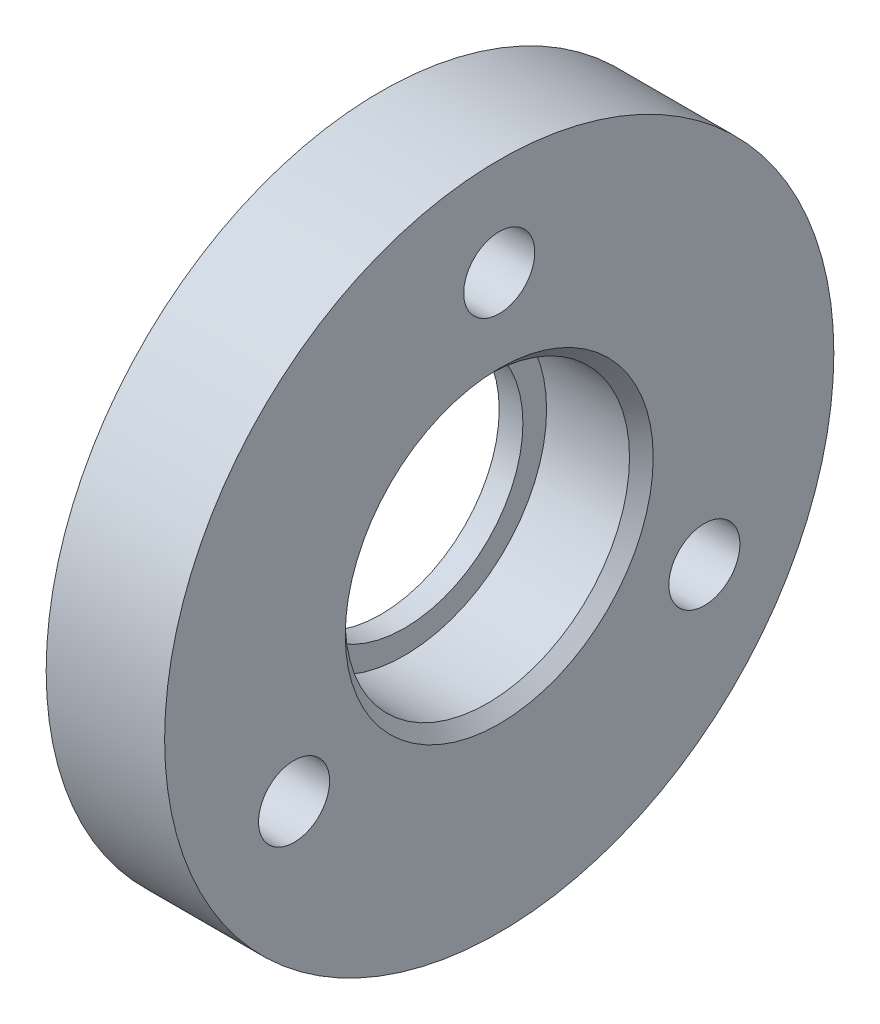
SolidWorks part; units mm, degrees
ref_plane "Front Plane" through (0, 0, 0) normal (1, 0, 0) x (0, 1, 0)
ref_plane "Top Plane" through (0, 0, 0) normal (0, 0, 1) x (0, 1, 0)
ref_plane "Right Plane" through (0, 0, 0) normal (0, 1, 0) x (-1, 0, 0)
sketch "Sketch3" plane through (0, 0, 0) normal (1, 0, 0) x (0, 1, 0)
  circle A0 centre (0, 0) radius 14.125
  circle A1 centre (0, 0) radius 6
  dimension "D1" = 28.25
  dimension "D2" = 12
extrude "Boss-Extrude1" add sketch "Sketch3" along normal blind 5
sketch "Sketch4" plane through (5, 0, 0) normal (1, 0, 0) x (0, 1, 0)
  circle A0 centre (0, 0) radius 5
  circle A1 centre (0, 0) radius 6
  circle A2 centre (0, 0) radius 6 construction
  dimension "D1" = 10
extrude "Boss-Extrude2" add sketch "Sketch4" along normal blind 1 from surface at -5 starting at face at (0, 0, -14.125)
sketch "Sketch5" plane through (5, 0, 0) normal (1, 0, 0) x (0, 0, -1)
  line L0 (0, -14.125) -> (0, 14.125) construction
  line L1 (0, 0) -> (-14.125, 0) construction
  circle A0 centre (0, 0) radius 14.125 construction
  circle A1 centre (0, 10) radius 1.5
  circle A2 centre (8.6603, -5) radius 1.5
  circle A3 centre (-8.6603, -5) radius 1.5
  point P7 (0, -10)
  point P8 (0, 10)
  point P18 (0, 0)
  dimension "D2" = 3
  dimension "D1" = 10
  dimension "D3" = 3
extrude "Cut-Extrude1" cut sketch "Sketch5" against normal blind 10
chamfer "Chamfer1" distance 0.5 angle 45 1 edges at (5, 0, -6)
